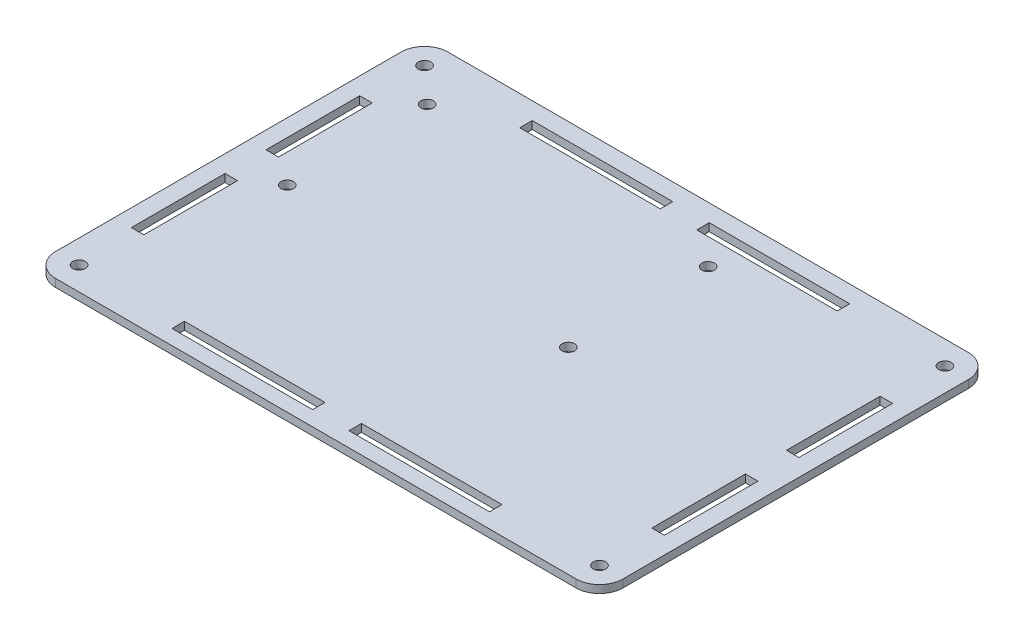
SolidWorks part; units mm, degrees
ref_plane "Front Plane" through (0, 0, 0) normal (0, 0, 1) x (1, 0, 0)
ref_plane "Top Plane" through (0, 0, 0) normal (0, 1, 0) x (1, 0, 0)
ref_plane "Right Plane" through (0, 0, 0) normal (1, 0, 0) x (0, 0, -1)
sketch "Sketch1" plane through (0, 0, 0) normal (0, 1, 0) x (1, 0, 0)
  line L0 (0, 8.1414) -> (0, -124047.6473) construction
  line L1 (0, 0) -> (145.34, 0)
  line L2 (0, 0) -> (0, 100.51)
  line L3 (0, 100.51) -> (145.34, 100.51)
  line L4 (145.34, 0) -> (145.34, 100.51)
  line L9 (3.753, 0) -> (124059.5417, 0) construction
  line L10 (12, 0) -> (12, -50000) construction
  line L11 (133.34, 0) -> (133.34, -50000) construction
  line L12 (0, 12) -> (-50000, 12) construction
  line L13 (-45.6158, 88.51) -> (49954.3842, 88.51) construction
  line L14 (-2.2542, 48) -> (-50002.2542, 48) construction
  line L15 (-71.6312, 38) -> (49928.3688, 38) construction
  line L16 (89.34, 114.3993) -> (89.34, -49885.6007) construction
  line L17 (60, 108.3918) -> (60, -49891.6082) construction
  line L18 (99.34, 117.8875) -> (99.34, -49882.1125) construction
  line L19 (32, 7.0141) -> (68, 7.0141)
  line L20 (32, 96.11) -> (68, 96.11)
  line L21 (32, 96.11) -> (32, 92.91)
  line L22 (32, 92.91) -> (68, 92.91)
  line L23 (68, 96.11) -> (68, 92.91)
  line L24 (113.34, 96.11) -> (77.34, 96.11)
  line L25 (113.34, 96.11) -> (113.34, 92.91)
  line L26 (113.34, 92.91) -> (77.34, 92.91)
  line L27 (77.34, 96.11) -> (77.34, 92.91)
  line L28 (32, 7.0141) -> (32, 3.8141)
  line L29 (32, 3.8141) -> (68, 3.8141)
  line L30 (68, 7.0141) -> (68, 3.8141)
  line L31 (113.34, 7.0141) -> (77.34, 7.0141)
  line L32 (113.34, 7.0141) -> (113.34, 3.8141)
  line L33 (113.34, 3.8141) -> (77.34, 3.8141)
  line L34 (77.34, 7.0141) -> (77.34, 3.8141)
  line L40 (4.4, 79.51) -> (7.6, 79.51)
  line L41 (4.4, 79.51) -> (4.4, 55.51)
  line L42 (4.4, 55.51) -> (7.6, 55.51)
  line L43 (7.6, 79.51) -> (7.6, 55.51)
  line L44 (4.4, 45) -> (7.6, 45)
  line L45 (4.4, 45) -> (4.4, 21)
  line L46 (4.4, 21) -> (7.6, 21)
  line L47 (7.6, 45) -> (7.6, 21)
  line L48 (137.74, 79.51) -> (140.94, 79.51)
  line L49 (137.74, 79.51) -> (137.74, 55.51)
  line L50 (137.74, 55.51) -> (140.94, 55.51)
  line L51 (140.94, 79.51) -> (140.94, 55.51)
  line L52 (137.74, 45) -> (140.94, 45)
  line L53 (137.74, 45) -> (137.74, 21)
  line L54 (137.74, 21) -> (140.94, 21)
  line L55 (140.94, 45) -> (140.94, 21)
  circle A1 centre (14.946, 86.224) radius 1.6
  circle A2 centre (86.952, 86.224) radius 1.6
  circle A3 centre (86.952, 50.413) radius 1.6
  circle A4 centre (14.946, 50.413) radius 1.6
  circle A7 centre (6, 94.51) radius 1.6
  circle A8 centre (139.34, 94.51) radius 1.6
  circle A9 centre (139.34, 6) radius 1.6
  circle A10 centre (6, 6) radius 1.6
  point P75 (0, 0)
  point P76 (0, 0)
  point P77 (0, 0)
  point P78 (0, 0)
  dimension "D14" = 14.946
  dimension "D16" = 86.952
  dimension "D22" = 6
  dimension "D24" = 6
  dimension "D26" = 6
  dimension "D28" = 6
  dimension "D1" = 100.51
  dimension "D2" = 145.34
  dimension "D3" = 12
  dimension "D4" = 12
  dimension "D5" = 12
  dimension "D6" = 12
  dimension "D7" = 40.51
  dimension "D8" = 10
  dimension "D9" = 26
  dimension "D10" = 29.34
  dimension "D11" = 48
  dimension "D12" = 10
  dimension "D13" = 34
  dimension "D15" = 14.286
  dimension "D17" = 14.946
  dimension "D18" = 50.097
  dimension "D19" = 10.51
  dimension "D23" = 6
  dimension "D25" = 6
  dimension "D27" = 6
  dimension "D29" = 6
  dimension "D30" = 36
  dimension "D31" = 20
  dimension "D32" = 3.2
  dimension "D33" = 36
  dimension "D34" = 20
  dimension "D35" = 20
  dimension "D36" = 3.2
  dimension "D37" = 20
  dimension "D38" = 36
  dimension "D39" = 36
  dimension "D40" = 24
  dimension "D41" = 9
  dimension "D42" = 9
  dimension "D43" = 24
  dimension "D44" = 24
  dimension "D45" = 24
  dimension "D46" = 9
  dimension "D47" = 9
extrude "Boss-Extrude1" add sketch "Sketch1" along normal blind 2
fillet "Fillet1" radius 6 1 edges at (0, 1, -100.51)
fillet "Fillet2" radius 6 1 edges at (0, 1, 0)
fillet "Fillet3" radius 6 2 edges at (145.34, 1, -100.51) (145.34, 1, 0)
